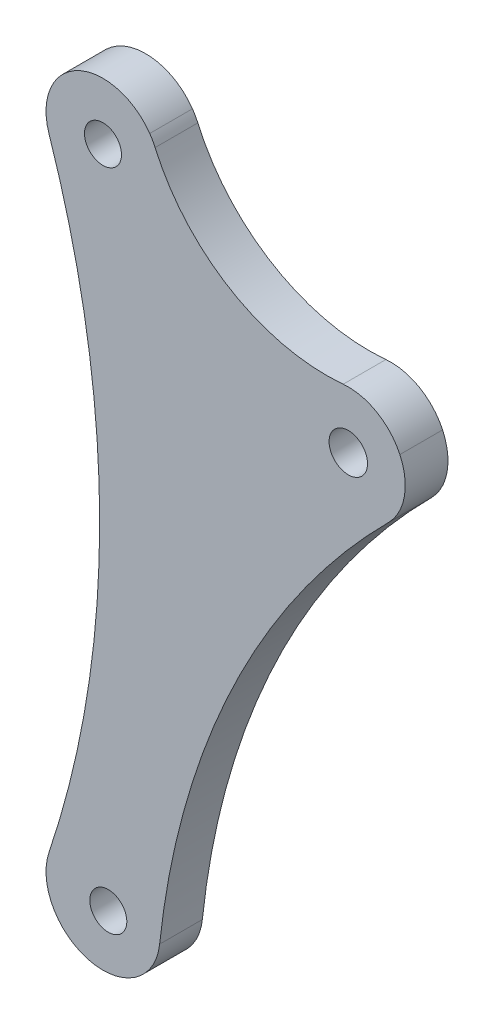
SolidWorks part; units mm, degrees
ref_plane "前视基准面" through (0, 0, 0) normal (0, 0, 1) x (1, 0, 0)
ref_plane "上视基准面" through (0, 0, 0) normal (0, 1, 0) x (1, 0, 0)
ref_plane "右视基准面" through (0, 0, 0) normal (1, 0, 0) x (0, 0, -1)
ref_plane "基准面1" through (0, 0, 3) normal (0, 0, 1) x (1, 0, 0)
sketch "草图1" plane through (0, 0, 3) normal (0, 0, 1) x (1, 0, 0)
  line L0 (-3.3131, 16.0217) -> (-3.3111, 16.0217)
  circle A0 centre (0.8533, -29.1662) radius 1.3
  circle A1 centre (0.4809, 17.2912) radius 1.3
  circle A2 centre (17.7114, 7.1362) radius 1.35
  arc A3 (-3.295, 15.9735) -> (-3.3131, -27.6933) centre (-68.6413, -5.8328) cw
  arc A4 (-3.3131, -27.6933) -> (-2.6616, -31.4376) centre (0.4832, -28.9615) ccw
  arc A5 (-2.6616, -31.4376) -> (1.8339, -32.7262) centre (0.48, -28.964) ccw
  arc A6 (1.8339, -32.7262) -> (4.4599, -29.3872) centre (0.4828, -28.9615) ccw
  arc A7 (4.4599, -29.3872) -> (20.5426, 4.3095) centre (60.2319, -35.3196) cw
  arc A8 (20.5426, 4.3095) -> (21.3336, 8.8325) centre (17.7095, 7.1357) ccw
  arc A9 (21.3336, 8.8325) -> (17.3516, 11.1205) centre (17.7088, 7.1331) ccw
  arc A10 (17.3516, 11.1205) -> (4.1406, 18.9075) centre (16.1693, 24.2148) cw
  arc A11 (4.1406, 18.9075) -> (3.7641, 19.5772) centre (0.4812, 17.2908) ccw
  arc A12 (3.7641, 19.5772) -> (-3.3131, 16.0217) centre (0.4811, 17.2907) ccw
  spline S0 degree 3 poles (-3.3111, 16.0217) (-3.3057, 16.0057) (-3.3004, 15.9896) (-3.295, 15.9735) knots 0 0 0 0 1 1 1 1
extrude "凸台-拉伸1" add sketch "草图1" against normal blind 3
